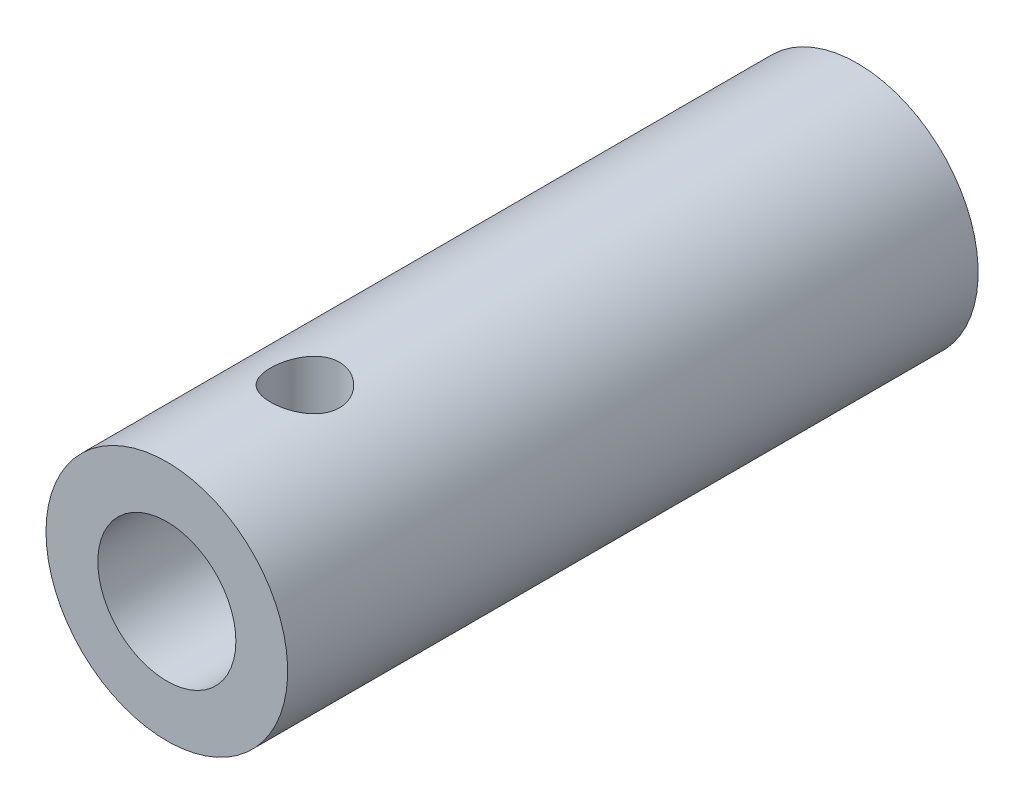
SolidWorks part; units mm, degrees
ref_plane "Front Plane" through (0, 0, 0) normal (0, 0, 1) x (1, 0, 0)
ref_plane "Top Plane" through (0, 0, 0) normal (0, 1, 0) x (1, 0, 0)
ref_plane "Right Plane" through (0, 0, 0) normal (1, 0, 0) x (0, 0, -1)
ref_plane "Plane1" through (0, 0, 0) normal (0, -1, 0) x (1, 0, 0)
sketch "Sketch1" plane through (0, 0, 0) normal (0, -1, 0) x (1, 0, 0)
  line L0 (7, 40) -> (0, 40)
  line L1 (0, 40) -> (0, 0)
  line L2 (0, 0) -> (7, 0)
  line L3 (7, 0) -> (7, 40)
  line L4 (0, 40) -> (0, 0) construction
revolve "Revolve1" add sketch "Sketch1" angle 360 about L4
hole_wizard "Ø8.0 (8) Diameter Hole1" positions "Sketch3" profile "Sketch2" hole size "Ø8.0" standard "ANSI Metric"
sketch "Sketch3" plane through (0, 0, 40) normal (0, 0, 1) x (1, 0, 0)
  point P0 (0, 0)
sketch "Sketch2" plane through (0, 0, 40) normal (1, 0, 0) x (0, -1, 0)
  line L0 (0, 0) -> (0, 40)
  line L1 (0, 40) -> (4, 40)
  line L2 (4, 40) -> (4, 0)
  line L5 (4, 0) -> (0, 0)
  line L11 (0, -6.35) -> (0, 107.95) construction
  dimension "Thru Hole Dia." = 8
  dimension "Thru Hole Depth" = 40
hole_wizard "Ø4.0 (4) Diameter Hole1" positions "3DSketch1" profile "Sketch4" hole size "Ø4.0" standard "ANSI Metric"
sketch3d "3DSketch1"
  point P0 (0, 7, 32)
sketch "Sketch4" plane through (0, 7, 32) normal (1, 0, 0) x (0, 0, 1)
  line L0 (0, 0) -> (0, 3)
  line L1 (0, 3) -> (2, 3)
  line L2 (2, 3) -> (2, 0)
  line L5 (2, 0) -> (0, 0)
  line L11 (0, -6.35) -> (0, 107.95) construction
  dimension "Thru Hole Dia." = 4
  dimension "Thru Hole Depth" = 3
